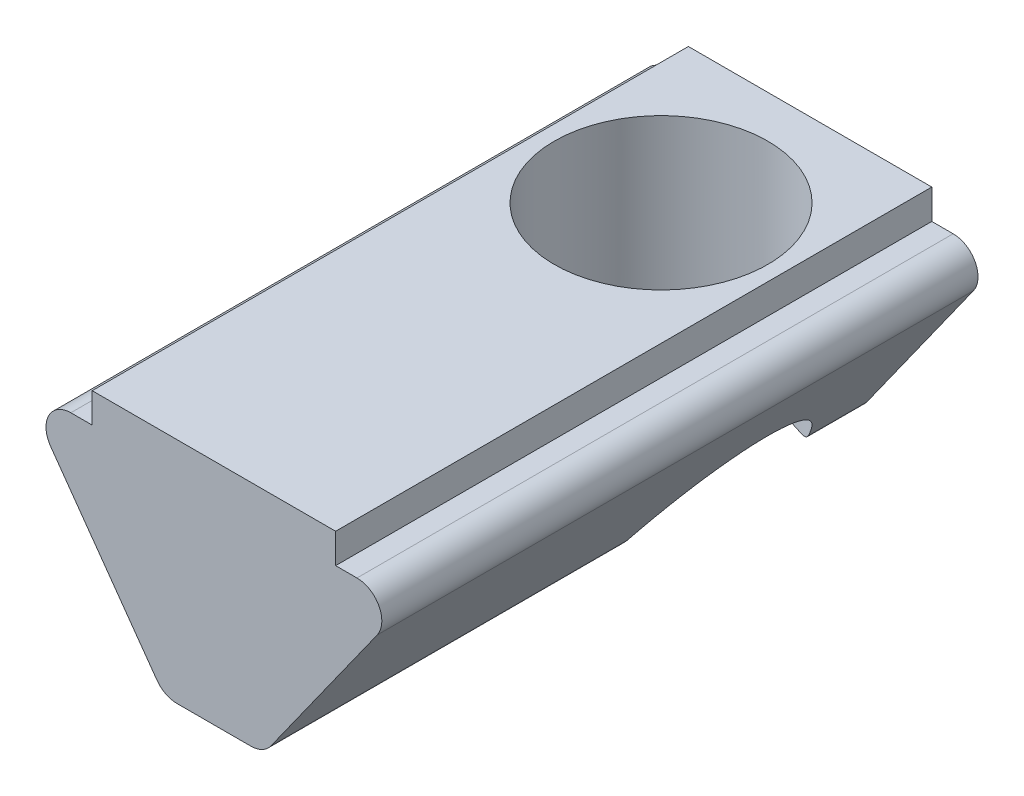
SolidWorks part; units mm, degrees
ref_plane "Plan de face" through (0, 0, 0) normal (0, 0, 1) x (1, 0, 0)
ref_plane "Plan de dessus" through (0, 0, 0) normal (0, 1, 0) x (1, 0, 0)
ref_plane "Plan de droite" through (0, 0, 0) normal (1, 0, 0) x (0, 0, -1)
sketch "Esquisse1" plane through (0, 0, 0) normal (0, 0, 1) x (1, 0, 0)
  line L0 (-2.45, 0) -> (2.45, 0)
  line L1 (2.45, 0) -> (2.45, -0.6)
  line L2 (2.45, -0.6) -> (3.85, -0.6)
  line L3 (3.85, -0.6) -> (1, -4.6)
  line L4 (1, -4.6) -> (-1, -4.6)
  line L5 (-1, -4.6) -> (-3.85, -0.6)
  line L6 (-3.85, -0.6) -> (-2.45, -0.6)
  line L7 (-2.45, -0.6) -> (-2.45, 0)
  line L8 (0, 0) -> (0, -4.6) construction
  point P11 (0, 0)
  point P12 (0, 0)
  point P13 (-4.2563, -0.6)
  point P14 (-3.405, -4.6)
  dimension "D1" = 4
  dimension "D2" = 0.6
  dimension "D3" = 4.9
  dimension "D4" = 7.7
  dimension "D5" = 2
extrude "Boss.-Extru.1" add sketch "Esquisse1" along normal mid plane 12
fillet "Congé1" radius 0.5 4 edges at (-3.85, -0.6, 0) (3.85, -0.6, 0) (1, -4.6, 0) (-1, -4.6, 0)
sketch "Esquisse2" plane through (0, 0, 0) normal (0, 1, 0) x (1, 0, 0)
  circle A0 centre (0, 3) radius 2.15
  dimension "D1" = 4.3
  dimension "D2" = 3
extrude "Enlèv. mat.-Extru.1" cut sketch "Esquisse2" against normal up to next
